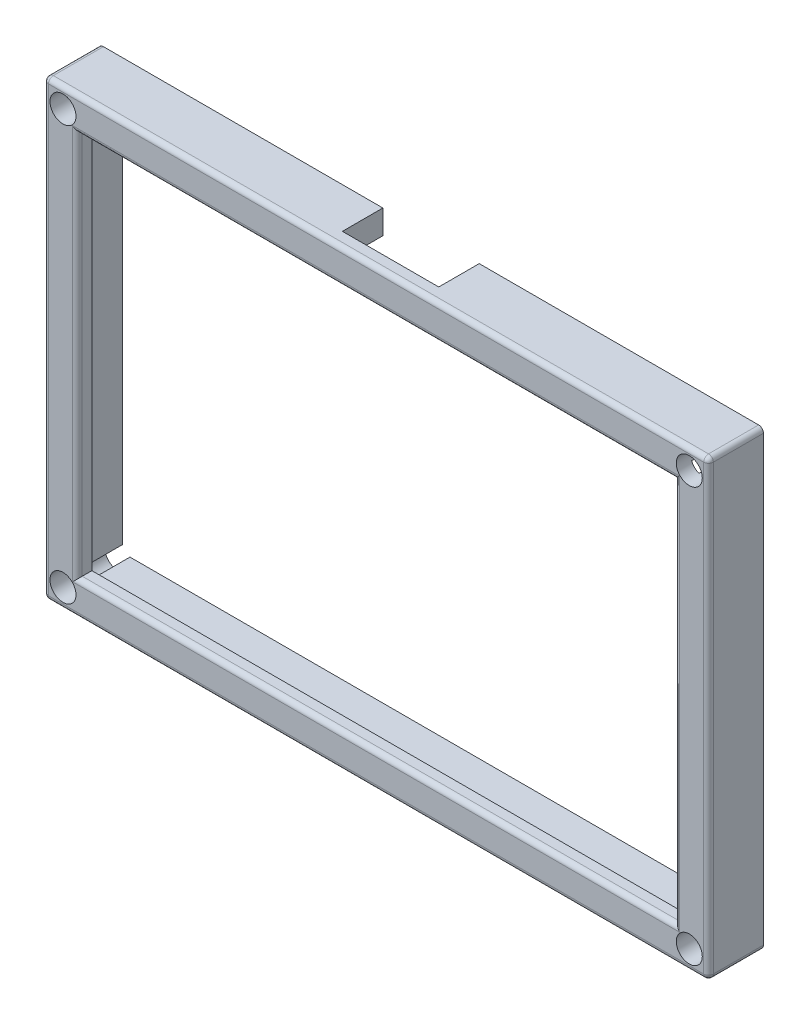
SolidWorks part; units mm, degrees
ref_plane "Front Plane" through (0, 0, 0) normal (0, 0, 1) x (1, 0, 0)
ref_plane "Top Plane" through (0, 0, 0) normal (0, 1, 0) x (1, 0, 0)
ref_plane "Right Plane" through (0, 0, 0) normal (1, 0, 0) x (0, 0, -1)
sketch "Sketch1" plane through (0, 0, 0) normal (0, 0, 1) x (1, 0, 0)
  line L0 (-34.5, 73.5) -> (34.5, 73.5)
  line L1 (-32.5, 71.5) -> (32.5, 71.5) construction
  line L2 (-32.5, 71.5) -> (-32.5, 28.5) construction
  line L3 (-32.5, 28.5) -> (32.5, 28.5) construction
  line L4 (32.5, 71.5) -> (32.5, 28.5) construction
  line L5 (34.5, 73.5) -> (34.5, 26.5)
  line L6 (-34.5, 26.5) -> (34.5, 26.5)
  line L7 (-34.5, 73.5) -> (-34.5, 26.5)
  line L8 (-32, 71) -> (32, 71)
  line L9 (32, 71) -> (32, 29)
  line L10 (-32, 29) -> (32, 29)
  line L11 (-32, 71) -> (-32, 29)
  line L12 (-5, 71.5) -> (-5, 81) construction
  line L13 (-5, 71) -> (-5, 73.5)
  line L14 (5, 71.5) -> (5, 81) construction
  line L15 (5, 71) -> (5, 73.5)
  circle A0 centre (-32.5, 71.5) radius 1.85 construction
  circle A1 centre (-32.5, 71.5) radius 1.85 construction
  circle A2 centre (-32.5, 28.5) radius 1.85 construction
  circle A3 centre (-32.5, 28.5) radius 1.85 construction
  circle A4 centre (32.5, 28.5) radius 1.85 construction
  circle A5 centre (32.5, 28.5) radius 1.85 construction
  circle A6 centre (32.5, 71.5) radius 1.85 construction
  circle A7 centre (32.5, 71.5) radius 1.85 construction
  circle A8 centre (-32.5, 71.5) radius 1.35
  circle A9 centre (32.5, 71.5) radius 1.35
  circle A10 centre (32.5, 28.5) radius 1.35
  circle A11 centre (-32.5, 28.5) radius 1.35
  point P28 (-5, 71)
  point P30 (-5, 73.5)
  point P32 (5, 73.5)
  point P34 (5, 71)
  dimension "D1" = 2.7
  dimension "D2" = 2
  dimension "D3" = 0.5
extrude "Boss-Extrude1" add sketch "Sketch1" along normal blind 4.2 contours L0 L7 L6 L5 A11 L11 A8 L8 A9 L9 A10 L10
sketch "Sketch2" plane through (0, 0, 4.2) normal (0, 0, 1) x (1, 0, 0)
  line L0 (34.5, 73.5) -> (34.5, 26.5) construction
  line L1 (-34.5, 26.5) -> (34.5, 26.5) construction
  line L2 (-34.5, 73.5) -> (-34.5, 26.5) construction
  line L4 (34.5, 73.5) -> (34.5, 26.5)
  line L5 (-34.5, 26.5) -> (34.5, 26.5)
  line L6 (-34.5, 73.5) -> (-34.5, 26.5)
  line L7 (-34.5, 73.5) -> (34.5, 73.5)
  line L8 (-31, 70) -> (31, 70)
  line L9 (31, 70) -> (31, 30)
  line L10 (-31, 30) -> (31, 30)
  line L11 (-31, 70) -> (-31, 30)
  arc A0 (-31.246, 71) -> (-32, 70.246) centre (-32.5, 71.5) ccw construction
  circle A1 centre (-32.5, 71.5) radius 1.35
  arc A2 (32, 70.246) -> (31.246, 71) centre (32.5, 71.5) ccw construction
  circle A3 centre (32.5, 71.5) radius 1.35
  arc A4 (31.246, 29) -> (32, 29.754) centre (32.5, 28.5) ccw construction
  circle A5 centre (32.5, 28.5) radius 1.35
  arc A6 (-32, 29.754) -> (-31.246, 29) centre (-32.5, 28.5) ccw construction
  circle A7 centre (-32.5, 28.5) radius 1.35
  point P11 (0, 0)
  point P12 (-31.9502, 70.246)
  point P17 (32.1374, 70.246)
  point P22 (32.148, 29.8033)
  point P27 (-31.1835, 28.7987)
  arc M5 (-31.246, 29) -> (-32, 29.754) centre (-32.5, 28.5) cw
  line M6 (-32, 29.754) -> (-32, 70.246)
  arc M7 (-32, 70.246) -> (-31.246, 71) centre (-32.5, 71.5) cw
  line M8 (-31.246, 71) -> (-5, 71)
  arc M9 (31.246, 71) -> (32, 70.246) centre (32.5, 71.5) cw
  line M10 (32, 70.246) -> (32, 29.754)
  arc M11 (32, 29.754) -> (31.246, 29) centre (32.5, 28.5) cw
  line M12 (31.246, 29) -> (-31.246, 29)
  line M13 (34.5, 73.5) -> (5, 73.5)
  line M14 (-34.5, 73.5) -> (-34.5, 26.5)
  line M15 (-34.5, 26.5) -> (34.5, 26.5)
  line M16 (34.5, 26.5) -> (34.5, 73.5)
  line M25 (-5, 71) -> (-5, 73.5)
  line M26 (-5, 73.5) -> (-34.5, 73.5)
  line M27 (5, 73.5) -> (5, 71)
  line M28 (5, 71) -> (31.246, 71)
  dimension "D1" = 3.5
extrude "Boss-Extrude2" add sketch "Sketch2" along normal blind 1.5 contours M12 M5 M6 M7 M8 M25 M26 M14 M15 M16 M13 M27 M28 M9 M10 M11 | A7 A5 A3 L7 A1 L11 L8 L9 L10 M12 M10 M28 M27 M25 M8 M6
fillet "Fillet1" radius 0.5 12 edges at (34.5, 73.5, 2.85) (-34.5, 73.5, 2.85) (-34.5, 26.5, 2.85) (34.5, 26.5, 2.85) (34.5, 50, 5.7) (0, 73.5, 5.7) (0, 26.5, 5.7) (-34.5, 50, 5.7) (0, 30, 5.7) (31, 50, 5.7) (0, 70, 5.7) (-31, 50, 5.7)
